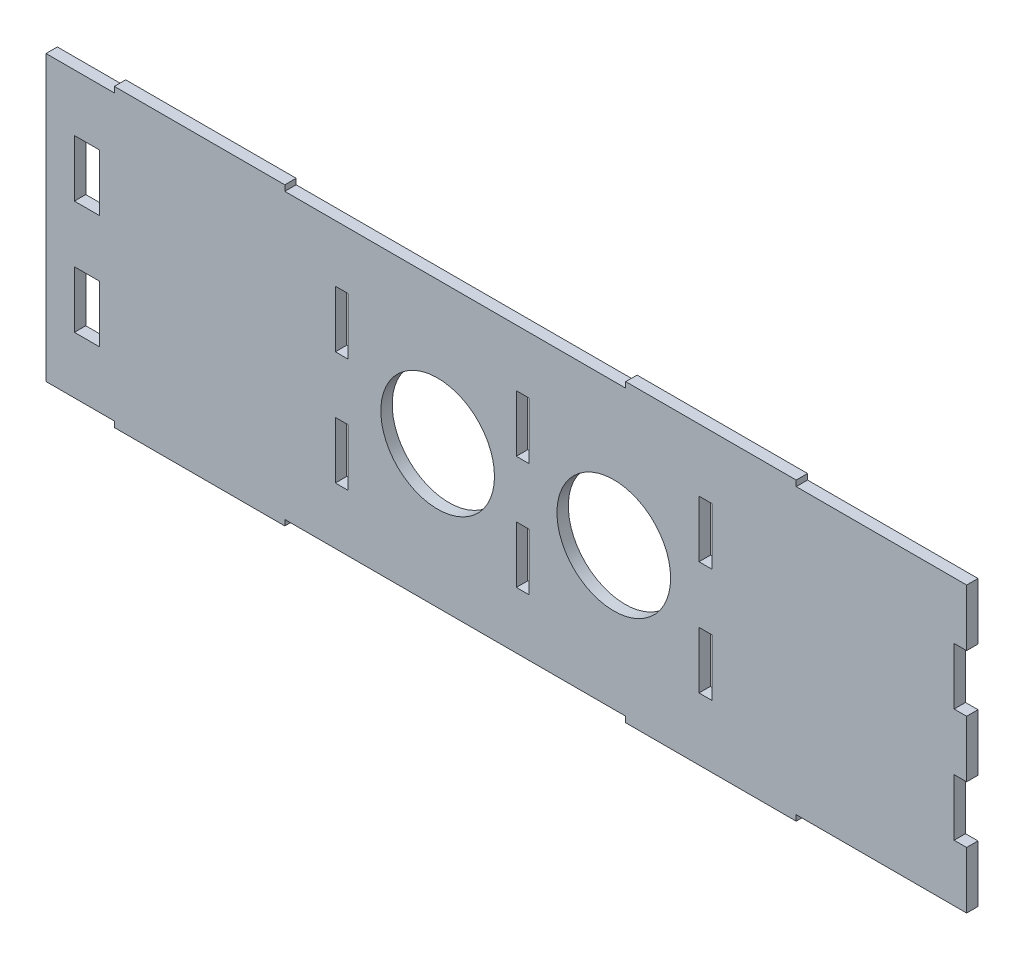
SolidWorks part; units mm, degrees
ref_plane "前视基准面" through (0, 0, 0) normal (0, 0, 1) x (1, 0, 0)
ref_plane "上视基准面" through (0, 0, 0) normal (0, 1, 0) x (1, 0, 0)
ref_plane "右视基准面" through (0, 0, 0) normal (1, 0, 0) x (0, 0, -1)
sketch "Model" plane through (0, 0, 0) normal (0, 0, 1) x (1, 0, 0)
  line L0 (13.9434, 55.1108) -> (18.9434, 55.1108)
  line L1 (18.9434, 55.1108) -> (18.9434, 56.1108)
  line L2 (18.9434, 56.1108) -> (48.9434, 56.1108)
  line L3 (48.9434, 56.1108) -> (48.9434, 55.1108)
  line L4 (48.9434, 55.1108) -> (108.9434, 55.1108)
  line L5 (108.9434, 55.1108) -> (108.9434, 56.1108)
  line L6 (108.9434, 56.1108) -> (138.9434, 56.1108)
  line L7 (138.9434, 56.1108) -> (138.9434, 55.1108)
  line L8 (138.9434, 55.1108) -> (168.9434, 55.1108)
  line L9 (168.9434, 55.1108) -> (168.9434, 45.1108)
  line L10 (168.9434, 45.1108) -> (166.7434, 45.1108)
  line L11 (166.7434, 45.1108) -> (166.7434, 35.1108)
  line L12 (166.7434, 35.1108) -> (168.9434, 35.1108)
  line L13 (168.9434, 35.1108) -> (168.9434, 25.1108)
  line L14 (168.9434, 25.1108) -> (166.7434, 25.1108)
  line L15 (166.7434, 25.1108) -> (166.7434, 15.1108)
  line L16 (166.7434, 15.1108) -> (168.9434, 15.1108)
  line L17 (168.9434, 15.1108) -> (168.9434, 5.1108)
  line L18 (168.9434, 5.1108) -> (138.9434, 5.1108)
  line L19 (138.9434, 5.1108) -> (138.9434, 4.1108)
  line L20 (138.9434, 4.1108) -> (108.9434, 4.1108)
  line L21 (108.9434, 4.1108) -> (108.9434, 5.1108)
  line L22 (108.9434, 5.1108) -> (61.9434, 5.1108)
  line L23 (61.9434, 5.1108) -> (55.9434, 5.1108)
  line L24 (55.9434, 5.1108) -> (48.9434, 5.1108)
  line L25 (48.9434, 5.1108) -> (48.9434, 4.1108)
  line L26 (48.9434, 4.1108) -> (18.9434, 4.1108)
  line L27 (89.6908, 25.1174) -> (91.8908, 25.1088)
  line L28 (91.8908, 25.1088) -> (91.8909, 15.1178)
  line L29 (91.8909, 15.1178) -> (89.6908, 15.1178)
  line L30 (89.6908, 15.1178) -> (89.6908, 25.1174)
  line L31 (89.6908, 45.1108) -> (91.8908, 45.1022)
  line L32 (91.8908, 45.1022) -> (91.8908, 35.1108)
  line L33 (91.8908, 35.1108) -> (89.6908, 35.1108)
  line L34 (89.6908, 35.1108) -> (89.6908, 45.1108)
  line L35 (121.8434, 45.1108) -> (124.1433, 45.1018)
  line L36 (124.1433, 45.1018) -> (124.1434, 35.1108)
  line L37 (124.1434, 35.1108) -> (121.8434, 35.1108)
  line L38 (121.8434, 35.1108) -> (121.8434, 45.1108)
  line L39 (121.8434, 25.1108) -> (124.1433, 25.1018)
  line L40 (124.1433, 25.1018) -> (124.1434, 15.1108)
  line L41 (124.1434, 15.1108) -> (121.8434, 15.1108)
  line L42 (121.8434, 15.1108) -> (121.8434, 25.1108)
  line L43 (57.8442, 45.1108) -> (60.0442, 45.1108)
  line L44 (57.8442, 35.1108) -> (60.0442, 35.1108)
  line L45 (57.8442, 25.1108) -> (60.0442, 25.1108)
  line L46 (57.8442, 15.1108) -> (60.0442, 15.1108)
  line L47 (57.8442, 45.1108) -> (57.8442, 35.1108)
  line L48 (60.0442, 45.1108) -> (60.0442, 35.1108)
  line L49 (57.8442, 25.1108) -> (57.8442, 15.1108)
  line L50 (60.0442, 25.1108) -> (60.0442, 15.1108)
  line L51 (18.9434, 5.1108) -> (6.9156, 5.1108)
  line L52 (18.9434, 5.1108) -> (18.9434, 4.1108)
  line L53 (6.9156, 55.1108) -> (13.9434, 55.1108)
  line L54 (11.9156, 35.1108) -> (16.3156, 35.1108)
  line L55 (11.9156, 25.1108) -> (16.3156, 25.1108)
  line L56 (11.9156, 45.1108) -> (16.3156, 45.1108)
  line L57 (11.9156, 15.1108) -> (16.3156, 15.1108)
  line L58 (11.9156, 45.1108) -> (11.9156, 35.1108)
  line L59 (11.9156, 25.1108) -> (11.9156, 15.1108)
  line L60 (16.3156, 15.1108) -> (16.3156, 25.1108)
  line L61 (16.3156, 45.1108) -> (16.3156, 35.1108)
  line L62 (6.9156, 55.1108) -> (6.9156, 5.1108)
  circle A0 centre (75.8434, 30.1108) radius 10
  circle A1 centre (106.8434, 30.1108) radius 10
extrude "凸台-拉伸1" add sketch "Model" along normal blind 2
